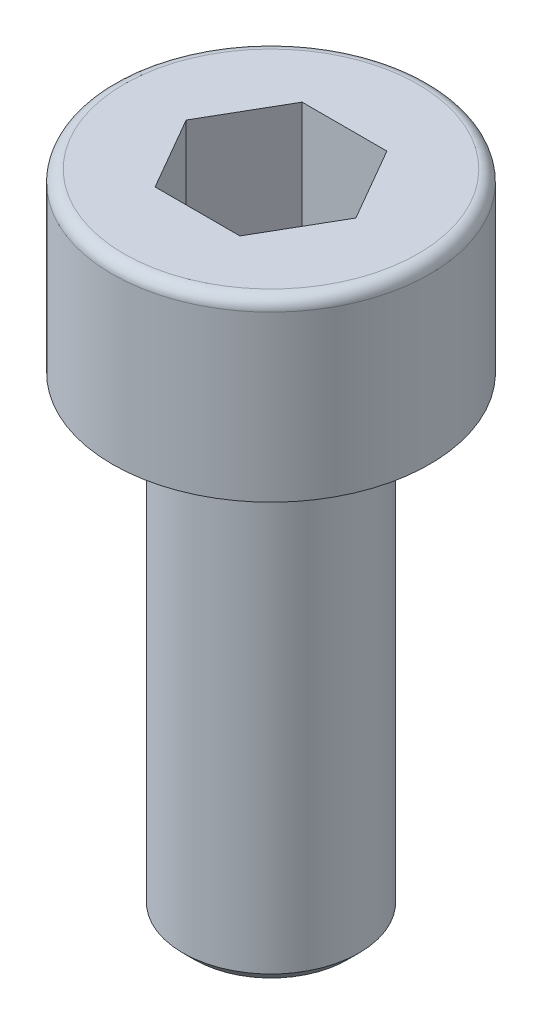
SolidWorks part; units mm, degrees
material "1023 Carbon Steel Sheet (SS)"
ref_plane "Front" through (0, 0, 0) normal (0, 0, 1) x (1, 0, 0)
ref_plane "Top" through (0, 0, 0) normal (0, 1, 0) x (1, 0, 0)
ref_plane "Right" through (0, 0, 0) normal (1, 0, 0) x (0, 0, -1)
sketch "Sketch1" plane through (0, 0, 0) normal (1, 0, 0) x (0, 0, -1)
  line L0 (0, 11.8275) -> (0, 0) construction
  line L1 (0, 0) -> (14.4314, 0) construction
  line L2 (0, 3) -> (0, -8)
  line L3 (0, -8) -> (1.3, -8)
  line L4 (1.3, -8) -> (1.5, -7.8)
  line L5 (1.5, -7.8) -> (1.5, -0.2)
  line L6 (1.7, 0) -> (2.7, 0)
  line L7 (2.7, 0) -> (2.7, 2.8)
  line L8 (2.5, 3) -> (0, 3)
  arc A0 (1.5, -0.2) -> (1.7, 0) centre (1.7, -0.2) cw
  arc A1 (2.7, 2.8) -> (2.5, 3) centre (2.5, 2.8) ccw
  dimension "D6" = 0.2
  dimension "D1" = 8
  dimension "D2" = 5.4
  dimension "D3" = 3
  dimension "D4" = 45
  dimension "D5" = 0.2
  dimension "D7" = 3
revolve "Revolve1" add sketch "Sketch1" angle 360 about L0
cosmetic thread "Cosmetic Thread1" parameters "D2"=2.439
sketch "Sketch2" plane through (0, 3, 0) normal (0, 1, 0) x (1, 0, 0)
  line L1 (0.7217, 1.25) -> (-0.7217, 1.25)
  line L2 (-0.7217, 1.25) -> (-1.4434, 0)
  line L3 (-1.4434, 0) -> (-0.7217, -1.25)
  line L4 (-0.7217, -1.25) -> (0.7217, -1.25)
  line L5 (0.7217, -1.25) -> (1.4434, 0)
  line L6 (1.4434, 0) -> (0.7217, 1.25)
  circle A0 centre (0, 0) radius 1.25 construction
  dimension "D1" = 2.5
extrude "Cut-Extrude1" cut sketch "Sketch2" against normal blind 2
equation "\"Screw Length\"= 8"
equation "\"D1@Sketch1\"=\"Screw Length\""
